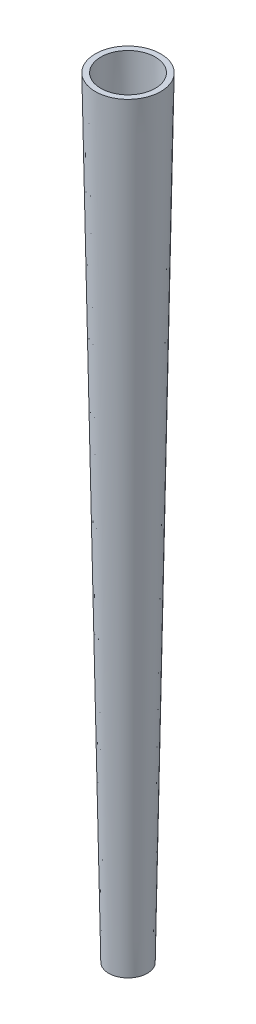
SolidWorks part; units mm, degrees
ref_plane "Front Plane" through (0, 0, 0) normal (0, 0, 1) x (1, 0, 0)
ref_plane "Top Plane" through (0, 0, 0) normal (0, 1, 0) x (1, 0, 0)
ref_plane "Right Plane" through (0, 0, 0) normal (1, 0, 0) x (0, 0, -1)
sketch "Sketch1" plane through (0, 0, 0) normal (0, 0, 1) x (1, 0, 0)
  line L0 (0, 0) -> (0, 140) construction
  line L1 (-2.5175, 1) -> (-4.9437, 140)
  line L2 (-123.5875, 0) -> (-19.0211, 0) construction
  line L3 (0, 140) -> (-5.9439, 140) construction
  line L4 (-5.9439, 140) -> (-3.5002, 0)
  line L5 (-3.5002, 0) -> (-2.5, 0)
  line L37 (-3.5002, 0) -> (0, 0) construction
  line L38 (-5.9439, 140) -> (-4.9437, 140)
  line L46 (-2.5, 0) -> (0, 0)
  line L47 (0, 0) -> (0, 1)
  line L48 (0, 1) -> (-2.5175, 1)
  dimension "D1" = 89
  dimension "D2" = 140
  dimension "D3" = 2.5
  dimension "D4" = 1
  dimension "D8" = 1
revolve "Revolve2" add sketch "Sketch1" angle 360 about L0
